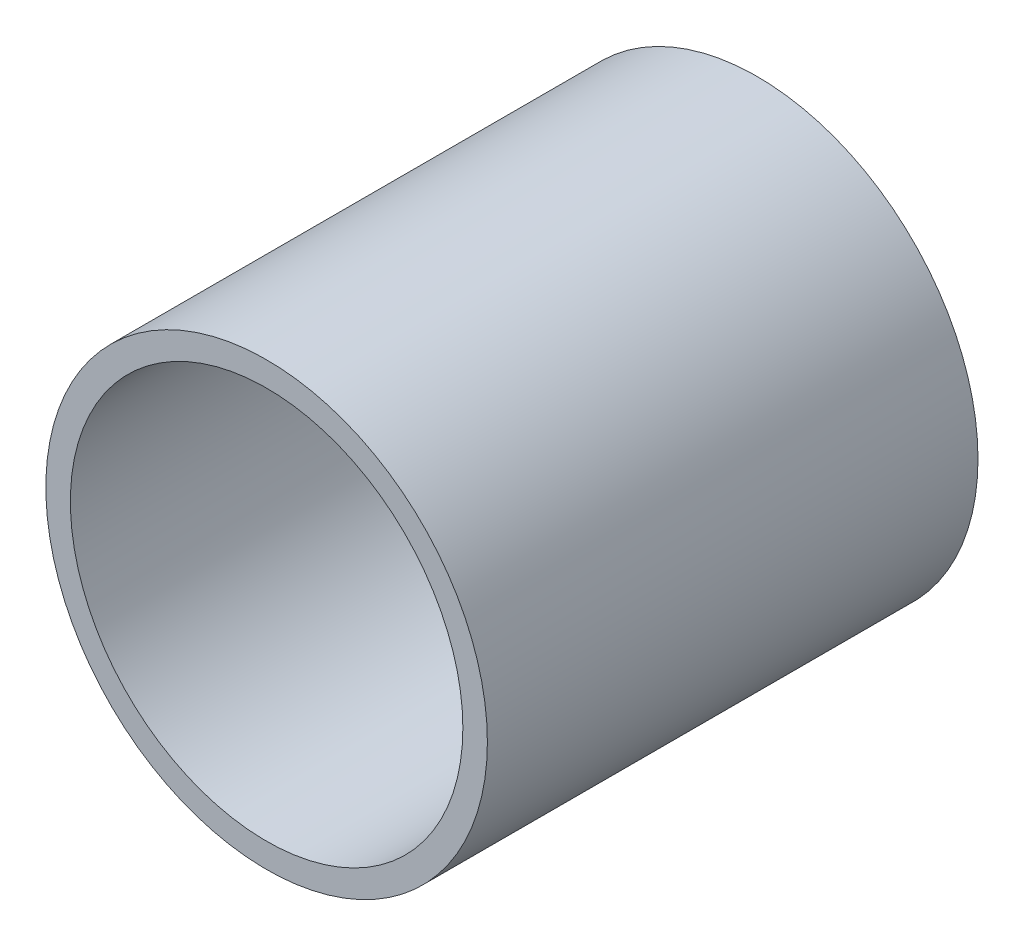
SolidWorks part; units mm, degrees
ref_plane "Ön Düzlem" through (0, 0, 0) normal (0, 0, 1) x (1, 0, 0)
ref_plane "Üst Düzlem" through (0, 0, 0) normal (0, 1, 0) x (1, 0, 0)
ref_plane "Sağ Düzlem" through (0, 0, 0) normal (1, 0, 0) x (0, 0, -1)
sketch "Çizim2" plane through (0, 0, 0) normal (0, 0, 1) x (1, 0, 0)
  circle A0 centre (0, 0) radius 16
  circle A1 centre (0, 0) radius 18
  dimension "D1" = 32
  dimension "D2" = 36
extrude "Yükseklik-Ekstrüzyon1" add sketch "Çizim2" along normal blind 40 contours A1 A0
